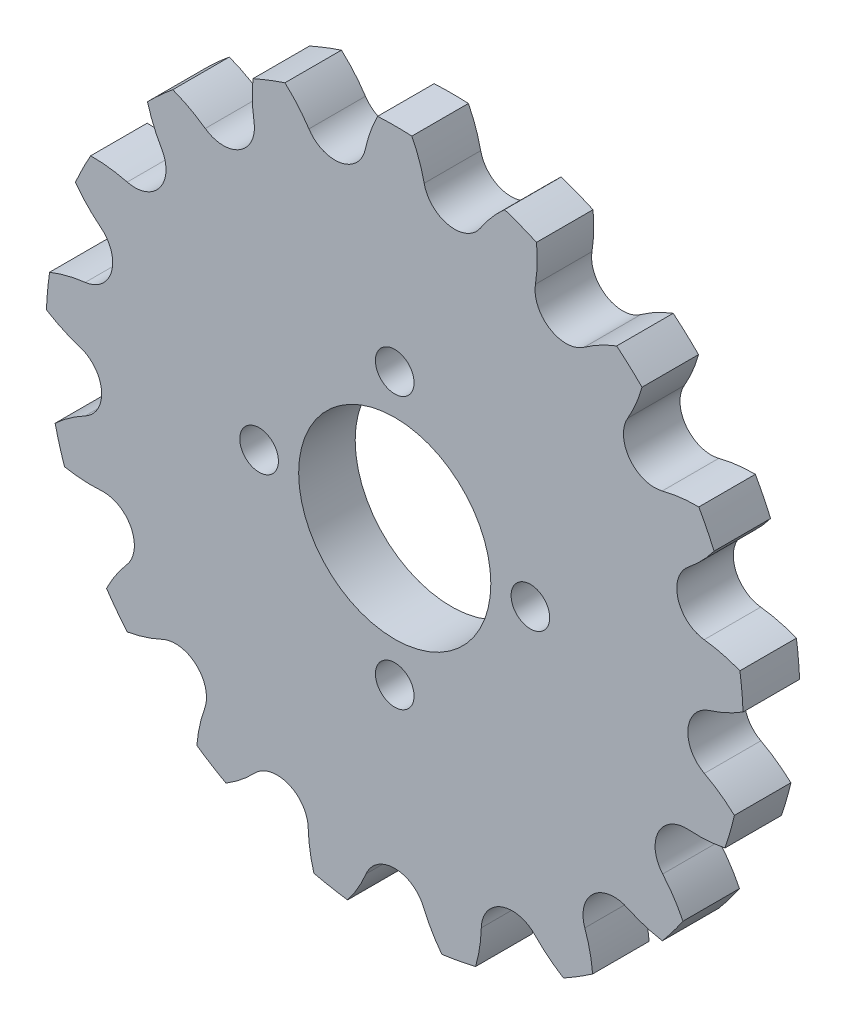
SolidWorks part; units mm, degrees
material "合金钢"
ref_plane "前视基准面" through (0, 0, 0) normal (0, 0, 1) x (1, 0, 0)
ref_plane "上视基准面" through (0, 0, 0) normal (0, 1, 0) x (1, 0, 0)
ref_plane "右视基准面" through (0, 0, 0) normal (1, 0, 0) x (0, 0, -1)
sketch "草图1" plane through (0, 0, 0) normal (0, 0, 1) x (1, 0, 0)
  line L0 (0, 15.63) -> (0, 27.7184) construction
  line L1 (2.872, 15.3639) -> (4.904, 26.2342) construction
  line L2 (-2.872, 15.3639) -> (-4.904, 26.2342) construction
  line L3 (-3.175, 16.9847) -> (3.175, 16.9847) construction
  line L4 (3.175, 16.9847) -> (-13.356, 13.4532) construction
  line L5 (3.175, 16.9847) -> (-5.7966, 15.0682) construction
  circle A0 centre (0, 0) radius 17.279 construction
  arc A1 (-11.7798, 14.2714) -> (-13.1236, 13.0463) centre (0, 0) ccw
  circle A2 centre (0, 0) radius 15.63 construction
  arc A5 (1.5624, 16.6403) -> (0.9092, 18.4826) centre (-5.7966, 15.0682) ccw
  arc A6 (1.5624, 16.6403) -> (2.872, 15.3639) centre (3.175, 16.9847) ccw
  arc A7 (-1.5624, 16.6403) -> (-0.9092, 18.4826) centre (5.7966, 15.0682) cw
  arc A8 (-1.5624, 16.6403) -> (-2.872, 15.3639) centre (-3.175, 16.9847) cw
  arc A9 (4.5542, 16.081) -> (5.8289, 17.563) centre (10.8484, 11.9567) cw
  arc A10 (4.5542, 16.081) -> (2.872, 15.3639) centre (3.175, 16.9847) cw
  arc A11 (7.4681, 14.9522) -> (8.2281, 13.2889) centre (9.0962, 14.6909) ccw
  arc A12 (7.4681, 14.9522) -> (7.5245, 16.9061) centre (0.0381, 16.1446) ccw
  arc A13 (10.0558, 13.3499) -> (11.7798, 14.2714) centre (14.4351, 7.2304) cw
  arc A14 (10.0558, 13.3499) -> (8.2281, 13.2889) centre (9.0962, 14.6909) cw
  arc A15 (12.3651, 11.2447) -> (12.473, 9.4192) centre (13.7889, 10.4129) ccw
  arc A16 (12.3651, 11.2447) -> (13.1236, 13.0463) centre (5.8676, 15.0406) ccw
  arc A17 (14.1993, 8.8158) -> (16.1397, 9.0523) centre (16.0722, 1.5276) cw
  arc A18 (14.1993, 8.8158) -> (12.473, 9.4192) centre (13.7889, 10.4129) cw
  arc A19 (15.5922, 6.0186) -> (15.0333, 4.2774) centre (16.6193, 4.7286) ccw
  arc A20 (15.5922, 6.0186) -> (16.9503, 7.4245) centre (10.9047, 11.9053) ccw
  arc A21 (16.4251, 3.0911) -> (18.3199, 2.6107) centre (15.5387, -4.3815) cw
  arc A22 (16.4251, 3.0911) -> (15.0333, 4.2774) centre (16.6193, 4.7286) cw
  arc A23 (16.7134, -0.0204) -> (15.5633, -1.4422) centre (17.2052, -1.5943) ccw
  arc A24 (16.7134, -0.0204) -> (18.4877, 0.8) centre (14.469, 7.1622) ccw
  arc A25 (16.4326, -3.051) -> (18.0259, -4.1835) centre (12.9066, -9.6989) cw
  arc A26 (16.4326, -3.051) -> (15.5633, -1.4422) centre (17.2052, -1.5943) cw
  arc A27 (15.5774, -6.0566) -> (13.9914, -6.9669) centre (15.4675, -7.7019) ccw
  arc A28 (15.5774, -6.0566) -> (17.5283, -5.9325) centre (16.0792, 1.4517) ccw
  arc A29 (14.2208, -8.7811) -> (15.2974, -10.4127) centre (8.5314, -13.7064) cw
  arc A30 (14.2208, -8.7811) -> (13.9914, -6.9669) centre (15.4675, -7.7019) cw
  arc A31 (12.3376, -11.2748) -> (10.5299, -11.5507) centre (11.6408, -12.7693) ccw
  arc A32 (12.3376, -11.2748) -> (14.2015, -11.8639) centre (15.5179, -4.4548) ccw
  arc A33 (10.0884, -13.3253) -> (10.5029, -15.2356) centre (3.004, -15.8627) cw
  arc A34 (10.0884, -13.3253) -> (10.5299, -11.5507) centre (11.6408, -12.7693) cw
  arc A35 (7.4316, -14.9703) -> (5.6462, -14.5745) centre (6.2419, -16.1121) ccw
  arc A36 (7.4316, -14.9703) -> (8.9568, -16.1929) centre (12.8607, -9.7597) ccw
  arc A37 (4.5935, -16.0698) -> (4.2899, -18.0009) centre (-2.9291, -15.8767) cw
  arc A38 (4.5935, -16.0698) -> (5.6462, -14.5745) centre (6.2419, -16.1121) cw
  arc A39 (1.5218, -16.644) -> (0, -15.63) centre (0, -17.279) ccw
  arc A40 (1.5218, -16.644) -> (2.5024, -18.335) centre (8.4666, -13.7465) ccw
  arc A41 (-1.5218, -16.644) -> (-2.5024, -18.335) centre (-8.4666, -13.7465) cw
  arc A42 (-1.5218, -16.644) -> (0, -15.63) centre (0, -17.279) cw
  arc A43 (-4.5935, -16.0698) -> (-5.6462, -14.5745) centre (-6.2419, -16.1121) ccw
  arc A44 (-4.5935, -16.0698) -> (-4.2899, -18.0009) centre (2.9291, -15.8767) ccw
  arc A45 (-7.4316, -14.9703) -> (-8.9568, -16.1929) centre (-12.8607, -9.7597) cw
  arc A46 (-7.4316, -14.9703) -> (-5.6462, -14.5745) centre (-6.2419, -16.1121) cw
  arc A47 (-10.0884, -13.3253) -> (-10.5299, -11.5507) centre (-11.6408, -12.7693) ccw
  arc A48 (-10.0884, -13.3253) -> (-10.5029, -15.2356) centre (-3.004, -15.8627) ccw
  arc A49 (-12.3376, -11.2748) -> (-14.2015, -11.8639) centre (-15.5179, -4.4548) cw
  arc A50 (-12.3376, -11.2748) -> (-10.5299, -11.5507) centre (-11.6408, -12.7693) cw
  arc A51 (-14.2208, -8.7811) -> (-13.9914, -6.9669) centre (-15.4675, -7.7019) ccw
  arc A52 (-14.2208, -8.7811) -> (-15.2974, -10.4127) centre (-8.5314, -13.7064) ccw
  arc A53 (-15.5774, -6.0566) -> (-17.5283, -5.9325) centre (-16.0792, 1.4517) cw
  arc A54 (-15.5774, -6.0566) -> (-13.9914, -6.9669) centre (-15.4675, -7.7019) cw
  arc A55 (-16.4326, -3.051) -> (-15.5633, -1.4422) centre (-17.2052, -1.5943) ccw
  arc A56 (-16.4326, -3.051) -> (-18.0259, -4.1835) centre (-12.9066, -9.6989) ccw
  arc A57 (-16.7134, -0.0204) -> (-18.4877, 0.8) centre (-14.469, 7.1622) cw
  arc A58 (-16.7134, -0.0204) -> (-15.5633, -1.4422) centre (-17.2052, -1.5943) cw
  arc A59 (-16.4251, 3.0911) -> (-15.0333, 4.2774) centre (-16.6193, 4.7286) ccw
  arc A60 (-16.4251, 3.0911) -> (-18.3199, 2.6107) centre (-15.5387, -4.3815) ccw
  arc A61 (-15.5922, 6.0186) -> (-16.9503, 7.4245) centre (-10.9047, 11.9053) cw
  arc A62 (-15.5922, 6.0186) -> (-15.0333, 4.2774) centre (-16.6193, 4.7286) cw
  arc A63 (-14.1993, 8.8158) -> (-12.473, 9.4192) centre (-13.7889, 10.4129) ccw
  arc A64 (-14.1993, 8.8158) -> (-16.1397, 9.0523) centre (-16.0722, 1.5276) ccw
  arc A65 (-12.3651, 11.2447) -> (-13.1236, 13.0463) centre (-5.8676, 15.0406) cw
  arc A66 (-12.3651, 11.2447) -> (-12.473, 9.4192) centre (-13.7889, 10.4129) cw
  arc A67 (-10.0558, 13.3499) -> (-8.2281, 13.2889) centre (-9.0962, 14.6909) ccw
  arc A68 (-10.0558, 13.3499) -> (-11.7798, 14.2714) centre (-14.4351, 7.2304) ccw
  arc A69 (-7.4681, 14.9522) -> (-7.5245, 16.9061) centre (-0.0381, 16.1446) cw
  arc A70 (-7.4681, 14.9522) -> (-8.2281, 13.2889) centre (-9.0962, 14.6909) cw
  arc A71 (-4.5542, 16.081) -> (-2.872, 15.3639) centre (-3.175, 16.9847) ccw
  arc A72 (-4.5542, 16.081) -> (-5.8289, 17.563) centre (-10.8484, 11.9567) ccw
  arc A73 (-5.8289, 17.563) -> (-7.5245, 16.9061) centre (0, 0) ccw
  arc A74 (0.9092, 18.4826) -> (-0.9092, 18.4826) centre (0, 0) ccw
  arc A75 (7.5245, 16.9061) -> (5.8289, 17.563) centre (0, 0) ccw
  arc A76 (13.1236, 13.0463) -> (11.7798, 14.2714) centre (0, 0) ccw
  arc A77 (16.9503, 7.4245) -> (16.1397, 9.0523) centre (0, 0) ccw
  arc A78 (18.4877, 0.8) -> (18.3199, 2.6107) centre (0, 0) ccw
  arc A79 (17.5283, -5.9325) -> (18.0259, -4.1835) centre (0, 0) ccw
  arc A80 (14.2015, -11.8639) -> (15.2974, -10.4127) centre (0, 0) ccw
  arc A81 (8.9568, -16.1929) -> (10.5029, -15.2356) centre (0, 0) ccw
  arc A82 (2.5024, -18.335) -> (4.2899, -18.0009) centre (0, 0) ccw
  arc A83 (-4.2899, -18.0009) -> (-2.5024, -18.335) centre (0, 0) ccw
  arc A84 (-10.5029, -15.2356) -> (-8.9568, -16.1929) centre (0, 0) ccw
  arc A85 (-15.2974, -10.4127) -> (-14.2015, -11.8639) centre (0, 0) ccw
  arc A86 (-18.0259, -4.1835) -> (-17.5283, -5.9325) centre (0, 0) ccw
  arc A87 (-18.3199, 2.6107) -> (-18.4877, 0.8) centre (0, 0) ccw
  arc A88 (-16.1397, 9.0523) -> (-16.9503, 7.4245) centre (0, 0) ccw
  point P181 (0, 0)
  dimension "D1" = 34.5579
  dimension "D2" = 37.01
  dimension "D3" = 31.26
  dimension "D5" = 67.353
  dimension "D6" = 9.174
  dimension "D7" = 17
  dimension "D4" = 10.588
extrude "凸台-拉伸2" add sketch "草图1" along normal blind 3
sketch "草图2" plane through (0, 0, 3) normal (0, 0, 1) x (1, 0, 0)
  circle A0 centre (0, 0) radius 7.2 construction
  circle A1 centre (0, 7.2) radius 1 construction
  circle A2 centre (7.2, 0) radius 1 construction
  circle A3 centre (0, -7.2) radius 1 construction
  circle A4 centre (-7.2, 0) radius 1 construction
  point P14 (0, 0)
  dimension "D1" = 14.4
  dimension "D2" = 2
  dimension "D3" = 4
hole_wizard "M2.5 螺纹孔1" positions "3D草图1" profile "草图3" tap size "M2.5" standard "GB" end condition up to next
sketch3d "3D草图1"
  point P0 (0, 7.2, 3)
  point P3 (7.2, 0, 3)
  point P6 (0, -7.2, 3)
  point P9 (-7.2, 0, 3)
sketch "草图3" plane through (0, 7.2, 3) normal (1, 0, 0) x (0, -1, 0)
  line L0 (0, 0) -> (0, 3)
  line L1 (0, 3) -> (1.025, 3)
  line L2 (1.025, 3) -> (1.025, 0)
  line L5 (1.025, 0) -> (0, 0)
  line L11 (0, -6.35) -> (0, 107.95) construction
  dimension "通孔螺纹孔钻头直径" = 2.05
  dimension "通孔螺纹孔钻头深度" = 3
cosmetic thread "孔螺蚊线5" parameters "D2"=2.5
cosmetic thread "孔螺蚊线6" parameters "D2"=2.5
cosmetic thread "孔螺蚊线7" parameters "D2"=2.5
cosmetic thread "孔螺蚊线8" parameters "D2"=2.5
sketch "草图4" plane through (0, 0, 0) normal (0, 0, -1) x (-1, 0, 0)
  circle A0 centre (0, 0) radius 5.1
  dimension "D1" = 10.2
extrude "切除-拉伸1" cut sketch "草图4" against normal blind 10
